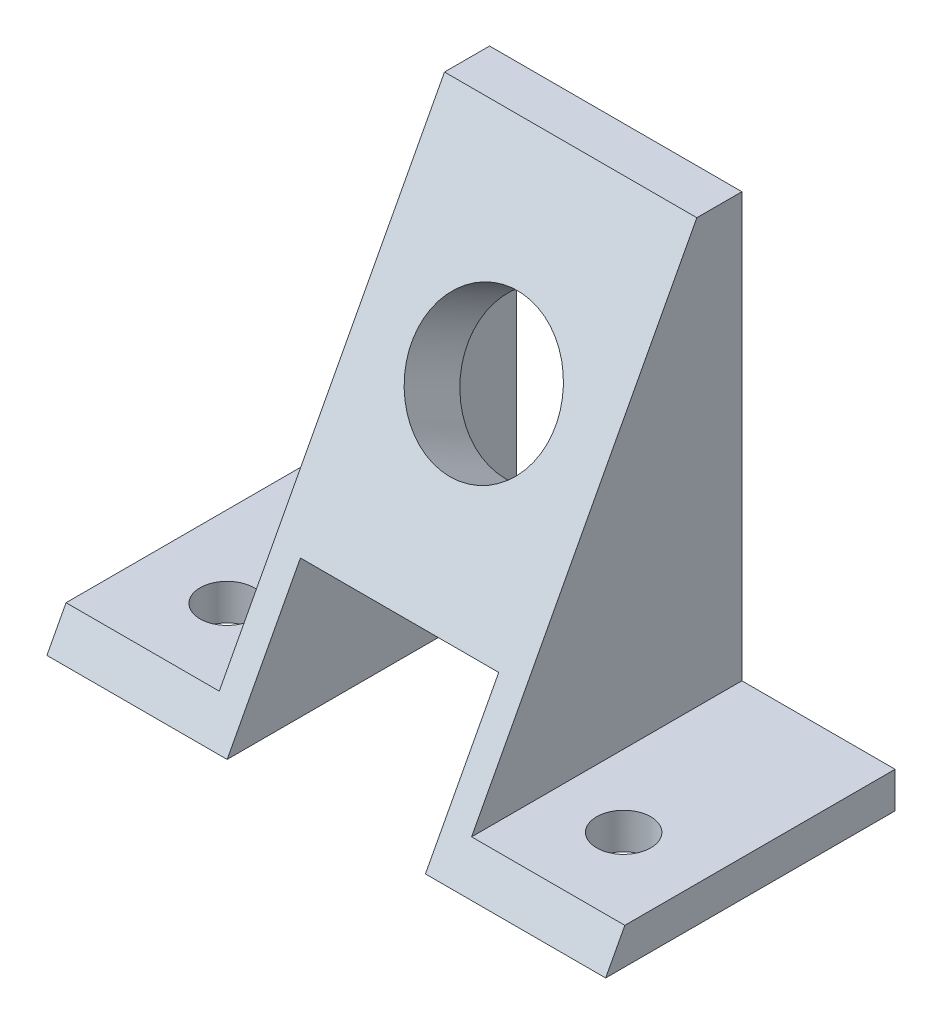
SolidWorks part; units mm, degrees
ref_plane "Front Plane" through (0, 0, 0) normal (0, 0, 1) x (1, 0, 0)
ref_plane "Top Plane" through (0, 0, 0) normal (0, 1, 0) x (1, 0, 0)
ref_plane "Right Plane" through (0, 0, 0) normal (1, 0, 0) x (0, 0, -1)
sketch "Sketch1" plane through (0, 0, 0) normal (1, 0, 0) x (0, 0, -1)
  line L0 (-13.8071, -7.6711) -> (13.3101, 43.3289)
  line L1 (13.3101, 43.3289) -> (13.3101, -7.6711)
  line L2 (13.3101, -7.6711) -> (-13.8071, -7.6711)
  dimension "D1" = 62
  dimension "D2" = 51
extrude "Boss-Extrude1" add sketch "Sketch1" along normal mid plane 28
sketch "Sketch4" plane through (0, 0, -13.3101) normal (0, 0, -1) x (-1, 0, 0)
  line L1 (-14, 43.3289) -> (14, 43.3289)
  line L2 (-14, 43.3289) -> (-14, -7.6711)
  line L3 (-14, -7.6711) -> (14, -7.6711)
  line L4 (14, 43.3289) -> (14, -7.6711)
extrude "Boss-Extrude2" add sketch "Sketch4" along normal blind 5
sketch "Sketch3" plane through (0, 4.0326, 7.5842) normal (0, 0.4695, 0.8829) x (1, 0, 0)
  circle A0 centre (0, 23.9706) radius 8
  dimension "D1" = 16
extrude "Cut-Extrude1" cut sketch "Sketch3" against normal through all
sketch "Sketch6" plane through (0, 0, 0) normal (1, 0, 0) x (0, 0, -1)
  line L0 (18.3101, 37.8222) -> (0.7638, 4.8224)
  line L1 (18.3101, 43.3289) -> (18.3101, -7.6711) construction
  line L3 (18.3101, 4.8224) -> (18.3101, 37.8222)
  line L4 (13.3101, 43.3289) -> (-13.8071, -7.6711) construction
  line L7 (0.7638, 4.8224) -> (0.7638, -14.665)
  line L8 (0.7638, -14.665) -> (18.3101, -14.665)
  line L9 (18.3101, 4.8224) -> (18.3101, -14.665)
  dimension "D1" = 7
extrude "Cut-Extrude3" cut sketch "Sketch6" against normal mid plane 22
sketch "Sketch7" plane through (0, 0, -0.7638) normal (0, 0, -1) x (-1, 0, 0)
  line L0 (11, 37.8222) -> (11, 4.8224) construction
  line L1 (-11, -7.6711) -> (11, -7.6711)
  line L2 (-11, -7.6711) -> (-11, 7.6255)
  line L3 (-11, 7.6255) -> (11, 7.6255)
  line L4 (11, -7.6711) -> (11, 7.6255)
extrude "Cut-Extrude4" cut sketch "Sketch7" against normal through all both and the other way through all
sketch "Sketch10" plane through (14, 0, 0) normal (1, 0, 0) x (0, 0, -1)
  line L0 (-13.8071, -7.6711) -> (-11.6803, -3.6711)
  line L1 (13.3101, 43.3289) -> (-13.8071, -7.6711) construction
  line L2 (-11.6803, -3.6711) -> (18.3101, -3.6711)
  line L3 (18.3101, 43.3289) -> (18.3101, -7.6711) construction
  line L4 (18.3101, -3.6711) -> (18.3101, -7.6711)
  line L5 (18.3101, -7.6711) -> (-13.8071, -7.6711)
  point P10 (-11.6803, -3.6711)
  dimension "D1" = 4
extrude "Boss-Extrude3" add sketch "Sketch10" along normal blind 17
mirror "Mirror5" about plane through (0, 0, 0) normal (1, 0, 0) of "Boss-Extrude3"
sketch "Sketch11" plane through (0, -7.6711, 0) normal (0, -1, 0) x (1, 0, 0)
  line L0 (0, -17.6644) -> (0, 17.6644) construction
  line L1 (31, 13.8071) -> (11, 13.8071) construction
  circle A0 centre (22, 2.8071) radius 3
  circle A1 centre (-22, 2.8071) radius 3
  dimension "D1" = 6
  dimension "D2" = 22
  dimension "D3" = 11
extrude "Cut-Extrude5" cut sketch "Sketch11" against normal through all both and the other way through all
